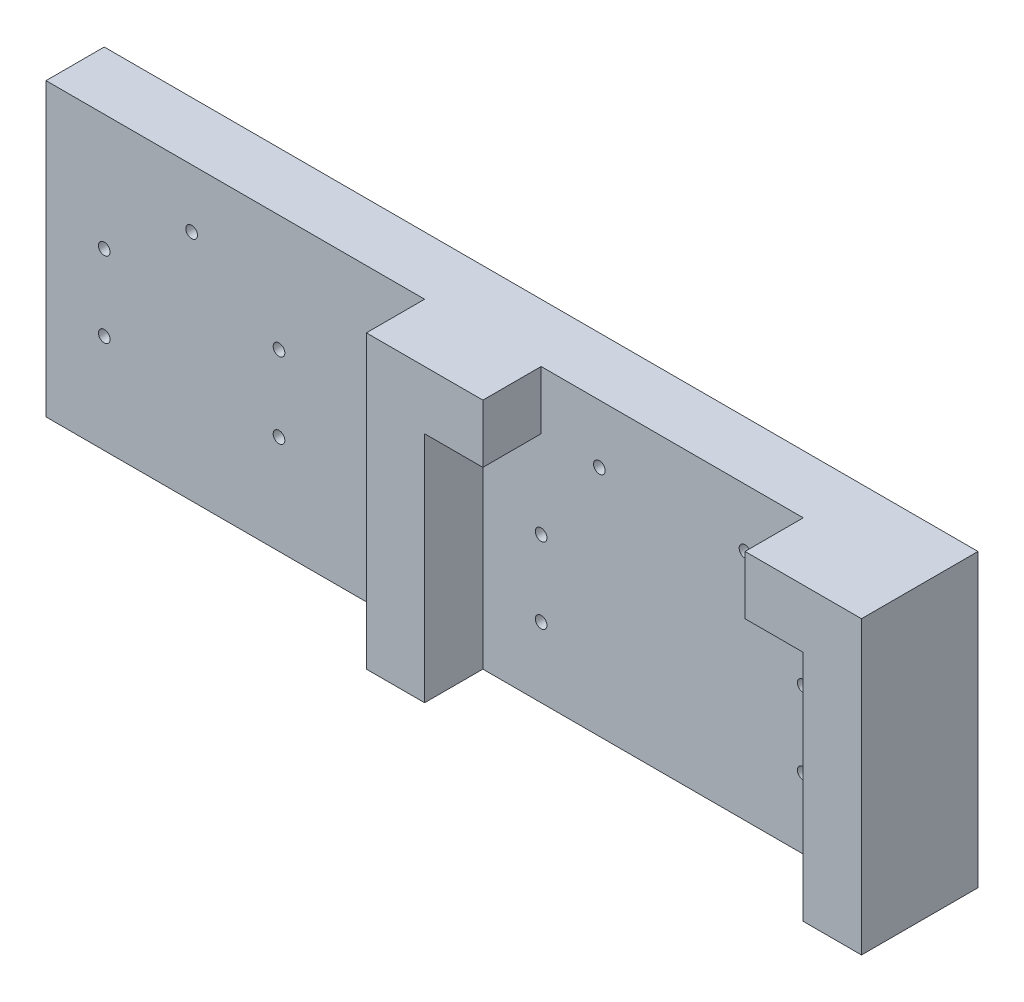
SolidWorks part; units mm, degrees
ref_plane "Plan de face" through (0, 0, 0) normal (0, 0, 1) x (1, 0, 0)
ref_plane "Plan de dessus" through (0, 0, 0) normal (0, 1, 0) x (1, 0, 0)
ref_plane "Plan de droite" through (0, 0, 0) normal (1, 0, 0) x (0, 0, -1)
sketch "Esquisse1" plane through (0, 0, -20) normal (0, 0, -1) x (-1, 0, 0)
  line L0 (-63.8586, -140.4642) -> (86.1414, -140.4642)
  line L1 (-63.8586, -140.4642) -> (-63.8586, -90.4642)
  line L2 (86.1414, -140.4642) -> (86.1414, -90.4642)
  line L3 (-63.8586, -90.4642) -> (86.1414, -90.4642)
  line L4 (1.1414, -100.4642) -> (11.1414, -100.4642) construction
  line L5 (-53.8586, -140.4642) -> (-53.8586, -100.4642) construction
  line L6 (11.1414, -140.4642) -> (-53.8586, -140.4642) construction
  circle A11 centre (-43.8586, -128.4642) radius 1
  circle A12 centre (-43.8586, -115.4642) radius 1
  circle A13 centre (-33.8586, -100.4642) radius 1
  circle A14 centre (-8.8586, -100.4642) radius 1
  circle A15 centre (1.1414, -115.4642) radius 1
  circle A16 centre (1.1414, -128.4642) radius 1
  circle A17 centre (46.1414, -123.4642) radius 1
  circle A18 centre (46.1414, -110.4642) radius 1
  circle A19 centre (61.1414, -100.4642) radius 1
  circle A20 centre (76.1414, -110.4642) radius 1
  circle A21 centre (76.1414, -123.4642) radius 1
  dimension "D4" = 2
  dimension "D5" = 2
  dimension "D6" = 2
  dimension "D7" = 2
  dimension "D8" = 2
  dimension "D9" = 2
  dimension "D10" = 2
  dimension "D11" = 2
  dimension "D12" = 2
  dimension "D13" = 2
  dimension "D14" = 2
  dimension "D1" = 150
  dimension "D2" = 10
  dimension "D3" = 10
extrude "Boss.-Extru.4" add sketch "Esquisse1" along normal blind 10
sketch "Esquisse3" plane through (0, 0, -20) normal (0, 0, 1) x (1, 0, 0)
  line L0 (63.8586, -90.4642) -> (43.8586, -90.4642)
  line L1 (63.8586, -90.4642) -> (63.8586, -140.4642)
  line L2 (43.8586, -90.4642) -> (43.8586, -140.4642)
  line L3 (63.8586, -140.4642) -> (43.8586, -140.4642)
  line L4 (-86.1414, -90.4642) -> (63.8586, -90.4642) construction
  line L5 (43.8586, 19.5358) -> (43.8586, -100.4642) construction
  line L6 (-1.1414, -90.4642) -> (-21.1414, -90.4642)
  line L7 (-1.1414, -90.4642) -> (-1.1414, -140.4642)
  line L8 (-21.1414, -90.4642) -> (-21.1414, -140.4642)
  line L9 (-1.1414, -140.4642) -> (-21.1414, -140.4642)
  line L10 (-1.1414, 19.5358) -> (-1.1414, -100.4642) construction
  line L11 (63.8586, -140.4642) -> (-86.1414, -140.4642) construction
  line L12 (-11.1414, -100.4642) -> (-11.1414, -125.4642) construction
  line L13 (-1.1414, -140.4642) -> (-11.1414, -140.4642)
  line L14 (-1.1414, -140.4642) -> (-1.1414, -100.4642)
  line L15 (-11.1414, -140.4642) -> (-11.1414, -100.4642)
  line L16 (-1.1414, -100.4642) -> (-11.1414, -100.4642)
  line L17 (43.8586, -140.4642) -> (53.8586, -140.4642)
  line L18 (43.8586, -140.4642) -> (43.8586, -100.4642)
  line L19 (53.8586, -140.4642) -> (53.8586, -100.4642)
  line L20 (43.8586, -100.4642) -> (53.8586, -100.4642)
  line M11 (63.8586, -140.4642) -> (63.8586, -90.4642)
  line M12 (63.8586, -90.4642) -> (-86.1414, -90.4642)
  line M14 (-86.1414, -140.4642) -> (63.8586, -140.4642)
  dimension "D1" = 10
extrude "Boss.-Extru.5" add sketch "Esquisse3" along normal blind 10 contours L16 L7 L8 L15 M12 M14 | L2 L20 L19 L3 M11 M12
